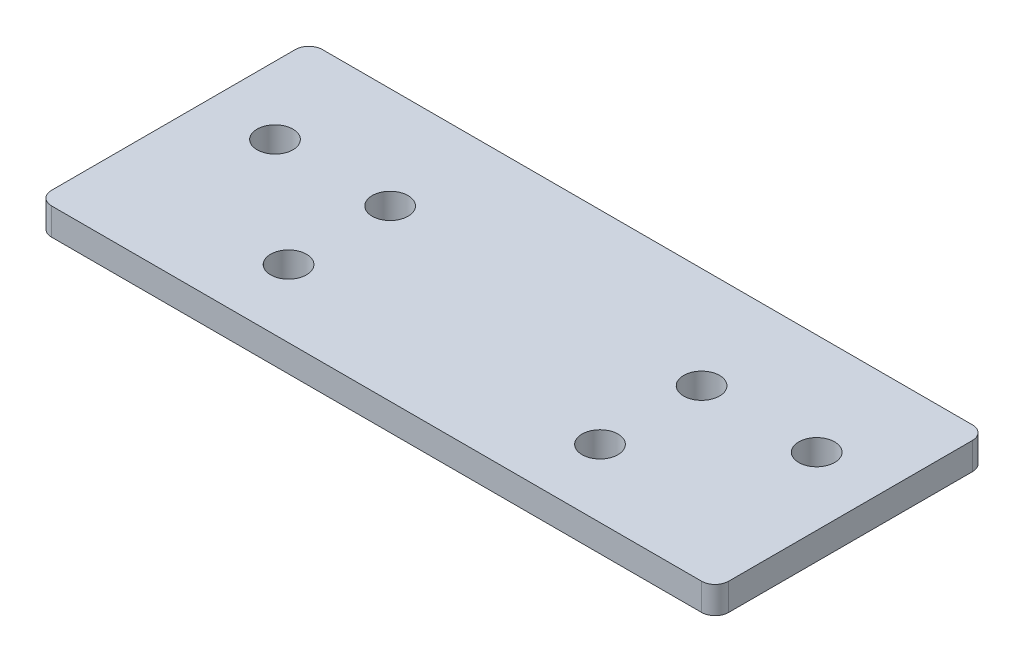
SolidWorks part; units mm, degrees
ref_plane "Front Plane" through (0, 0, 0) normal (0, 0, 1) x (1, 0, 0)
ref_plane "Top Plane" through (0, 0, 0) normal (0, 1, 0) x (1, 0, 0)
ref_plane "Right Plane" through (0, 0, 0) normal (1, 0, 0) x (0, 0, -1)
sketch "Sketch1" plane through (0, 0, 0) normal (0, 1, 0) x (1, 0, 0)
  line L1 (50, -20) -> (-50, -20)
  line L2 (50, -20) -> (50, 20)
  line L3 (50, 20) -> (-50, 20)
  line L4 (-50, -20) -> (-50, 20)
  line L5 (50, -20) -> (-50, 20) construction
  line L6 (50, 20) -> (-50, -20) construction
  point P0 (0, 0)
  dimension "D7" = 100
  dimension "D8" = 40
extrude "Boss-Extrude1" add sketch "Sketch1" along normal blind 4
fillet "Fillet1" radius 2 4 edges at (50, 2, 20) (50, 2, -20) (-50, 2, -20) (-50, 2, 20)
hole_wizard "M5 Clearance Hole1" positions "Sketch3" profile "Sketch2" hole size "M5" standard "ISO"
sketch "Sketch3" plane through (0, 4, 0) normal (0, 1, 0) x (1, 0, 0)
  line L0 (-42.2687, 0) -> (56.8217, 0) construction
  line L1 (-55, 0) -> (55, 0) construction
  line L3 (0, 18.8846) -> (0, -31.0081) construction
  line L4 (0, -55) -> (0, 55) construction
  line L5 (48, 20) -> (-48, 20) construction
  point P0 (-40, 5)
  point P2 (-23, 5)
  point P20 (-23, -10)
  point P23 (23, -10)
  point P24 (23, 5)
  point P25 (40, 5)
  dimension "D1" = 80
  dimension "D2" = 15
  dimension "D3" = 23
  dimension "D4" = 15
sketch "Sketch2" plane through (-40, 4, -5) normal (1, 0, 0) x (0, 0, 1)
  line L0 (0, 0) -> (0, 9.5923)
  line L1 (0, 9.5923) -> (2.65, 8)
  line L2 (2.65, 8) -> (2.65, 0)
  line L5 (2.65, 0) -> (0, 0)
  line L10 (0, 9.5923) -> (-2.65, 8) construction
  line L11 (0, -6.35) -> (0, 107.95) construction
  dimension "Hole Dia." = 5.3
  dimension "Hole Depth" = 8
  dimension "Drill Angle" = 118
